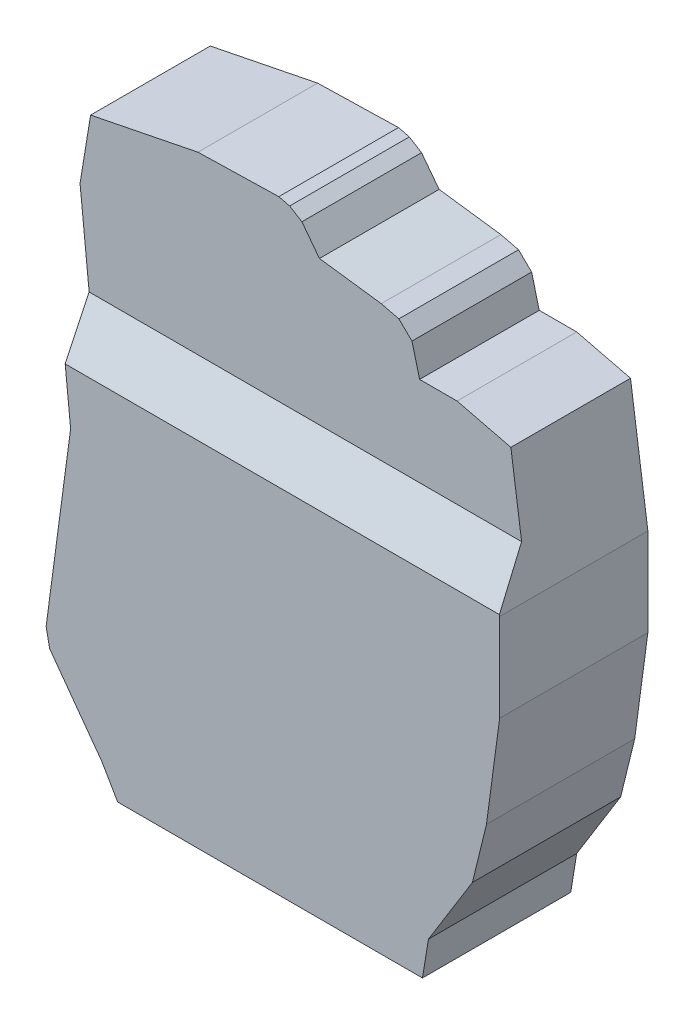
SolidWorks part; units mm, degrees
ref_plane "Front Plane" through (0, 0, 0) normal (0, 0, 1) x (1, 0, 0)
ref_plane "Top Plane" through (0, 0, 0) normal (0, 1, 0) x (1, 0, 0)
ref_plane "Right Plane" through (0, 0, 0) normal (1, 0, 0) x (0, 0, -1)
sketch "Sketch1" plane through (0, 0, 0) normal (0, 0, 1) x (1, 0, 0)
  line L0 (6.2196, 20.172) -> (31.0978, 20.172) construction
  line L16 (546.873, 9.9176) -> (893.0858, 9.9176) construction
  line L17 (543.5946, 13.7694) -> (705.2646, 13.7694) construction
  line L43 (547.2066, 9.9086) -> (608.8766, 9.9086) construction
  line L44 (546.5809, 9.8961) -> (608.2509, 9.8961)
  line L45 (608.2509, 9.8961) -> (609.4687, 17.3252)
  line L46 (609.4687, 17.3252) -> (618.3641, 31.6987)
  line L47 (618.3641, 31.6987) -> (621.2095, 43.3087)
  line L48 (621.2095, 43.3087) -> (623.8684, 63.2242)
  line L49 (623.8684, 63.2242) -> (623.8684, 81.0545)
  line L50 (623.8684, 81.0545) -> (620.3573, 106.0595)
  line L51 (620.3573, 106.0595) -> (609.4687, 108.7281)
  line L52 (609.4687, 108.7281) -> (601.8876, 108.7281)
  line L53 (601.8876, 108.7281) -> (600.3424, 114.6689)
  line L54 (600.3424, 114.6689) -> (597.6933, 117.2443)
  line L55 (597.6933, 117.2443) -> (594.1218, 118.1197)
  line L56 (594.1218, 118.1197) -> (581.6232, 119.7883)
  line L57 (581.6232, 119.7883) -> (578.0652, 124.4428)
  line L58 (578.0652, 124.4428) -> (575.593, 125.9728)
  line L59 (575.593, 125.9728) -> (573.398, 126.5107)
  line L60 (573.398, 126.5107) -> (557.03, 126.1181)
  line L61 (557.03, 126.1181) -> (535.3097, 121.7603)
  line L62 (535.3097, 121.7603) -> (533.8832, 113.0576)
  line L63 (533.8832, 113.0576) -> (533.1735, 108.7281)
  line L64 (533.1735, 108.7281) -> (536.3202, 77.7869)
  line L65 (536.3202, 77.7869) -> (537.0549, 70.5624)
  line L66 (537.0549, 70.5624) -> (532.0987, 33.4394)
  line L67 (532.0987, 33.4394) -> (532.8106, 29.8912)
  line L68 (532.8106, 29.8912) -> (543.389, 15.3737)
  line L69 (543.389, 15.3737) -> (546.5809, 9.8961)
extrude "Boss-Extrude1" add sketch "Sketch1" along normal blind 30
ref_plane "Plane1" through (530, 0, 0) normal (1, 0, 0) x (0, 0, -1)
sketch "Sketch2" plane through (530, 0, 0) normal (1, 0, 0) x (0, 0, -1)
  line L0 (-24.212, 126.5107) -> (-24.212, 90.6107)
  line L1 (-30, 126.5107) -> (0, 126.5107) construction
  line L2 (-24.212, 90.6107) -> (-30, 81.3731)
  line L3 (-30, 108.7281) -> (-30, 70.5624) construction
  line L4 (-24.212, 90.6107) -> (-24.212, 79.6081) construction
  line L5 (-24.212, 126.5107) -> (-30, 126.5107)
  line L7 (-30, 126.5107) -> (-30, 81.3731)
  dimension "D1" = 35.9
  dimension "D2" = 5.788
  dimension "D3" = 32.07
extrude "Cut-Extrude2" cut sketch "Sketch2" against normal through all both and the other way through all
